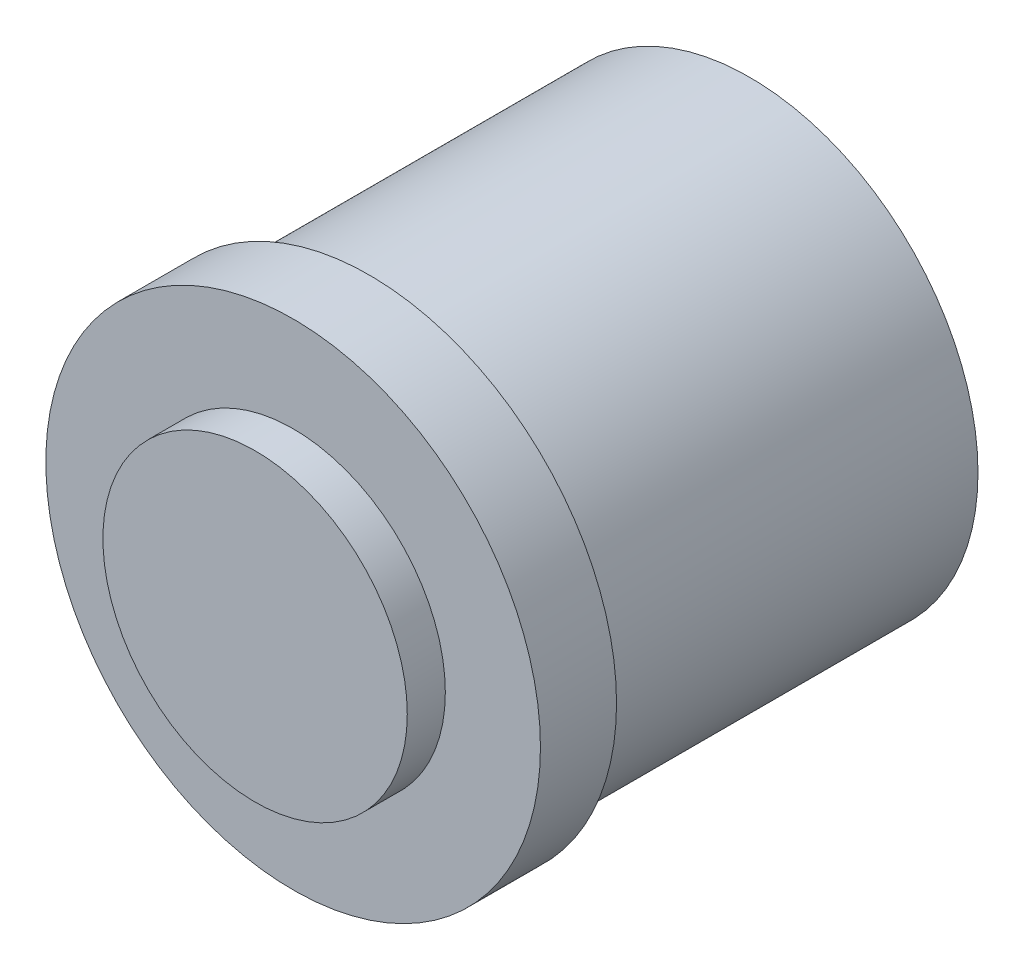
SolidWorks part; units mm, degrees
material "Oak"
ref_plane "Front" through (0, 0, 0) normal (0, 0, 1) x (1, 0, 0)
ref_plane "Top" through (0, 0, 0) normal (0, 1, 0) x (1, 0, 0)
ref_plane "Right" through (0, 0, 0) normal (1, 0, 0) x (0, 0, -1)
sketch "Sketch1" plane through (0, 0, 0) normal (0, 0, 1) x (1, 0, 0)
  circle A0 centre (0, 0) radius 38.1
  dimension "D1" = 76.2
extrude "Boss-Extrude1" add sketch "Sketch1" along normal blind 63.5
sketch "Sketch2" plane through (0, 0, 63.5) normal (0, 0, 1) x (1, 0, 0)
  circle A0 centre (0, 0) radius 41.275
  dimension "D1" = 82.55
extrude "Boss-Extrude2" add sketch "Sketch2" along normal blind 12.7
sketch "Sketch3" plane through (0, 0, 76.2) normal (0, 0, 1) x (1, 0, 0)
  circle A0 centre (0, 0) radius 25.4
  dimension "D1" = 50.8
extrude "Boss-Extrude3" add sketch "Sketch3" along normal blind 6.35
